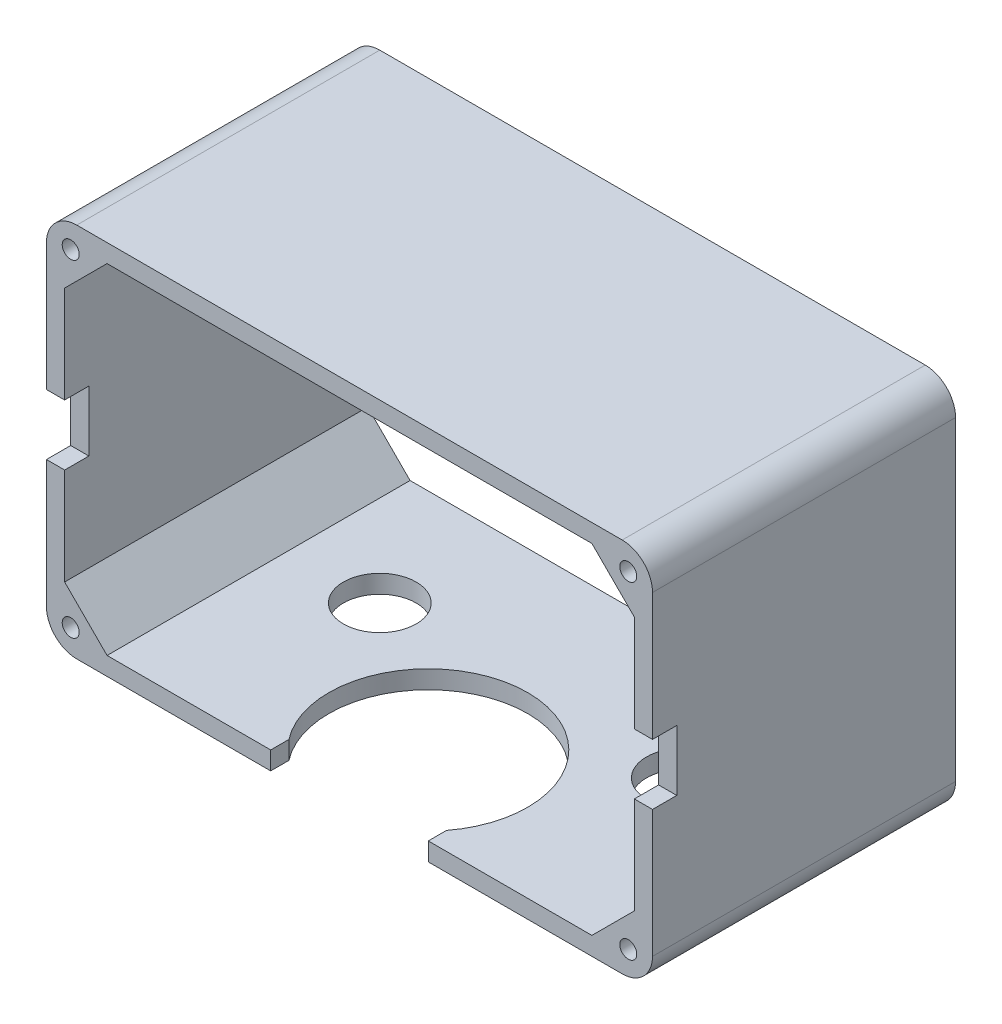
SolidWorks part; units mm, degrees
ref_plane "前视基准面" through (0, 0, 0) normal (0, 0, 1) x (1, 0, 0)
ref_plane "上视基准面" through (0, 0, 0) normal (0, 1, 0) x (1, 0, 0)
ref_plane "右视基准面" through (0, 0, 0) normal (1, 0, 0) x (0, 0, -1)
other "Configuration Table"
sketch "草图1" plane through (0, 0, 0) normal (0, 0, 1) x (1, 0, 0)
  line L1 (-45, 31) -> (45, 31)
  line L2 (-50, 26) -> (-50, -26)
  line L3 (-45, -31) -> (45, -31)
  line L4 (50, 26) -> (50, -26)
  line L5 (-50, 31) -> (50, -31) construction
  line L6 (-50, -31) -> (50, 31) construction
  line L7 (-42, 28) -> (42, 28)
  line L8 (-47, 23) -> (-47, -23)
  line L9 (-42, -28) -> (42, -28)
  line L10 (47, 23) -> (47, -23)
  line L11 (-47, 28) -> (47, -28) construction
  line L12 (-47, -28) -> (47, 28) construction
  arc A0 (-50, 26) -> (-45, 31) centre (-45, 26) cw
  arc A1 (50, 26) -> (45, 31) centre (45, 26) ccw
  arc A2 (45, -31) -> (50, -26) centre (45, -26) ccw
  arc A3 (-45, -31) -> (-50, -26) centre (-45, -26) cw
  arc A4 (-47, 23) -> (-42, 28) centre (-42, 23) cw
  arc A5 (47, 23) -> (42, 28) centre (42, 23) ccw
  arc A6 (42, -28) -> (47, -23) centre (42, -23) ccw
  arc A7 (-42, -28) -> (-47, -23) centre (-42, -23) cw
  point P0 (0, 0)
  point P18 (0, 0)
  dimension "D3" = 5
  dimension "D4" = 5
  dimension "D5" = 5
  dimension "D6" = 5
  dimension "D9" = 5
  dimension "D10" = 5
  dimension "D11" = 5
  dimension "D12" = 5
  dimension "D1" = 100
  dimension "D2" = 62
  dimension "D7" = 94
  dimension "D8" = 56
extrude "凸台-拉伸1" add sketch "草图1" along normal blind 50
sketch "草图3" plane through (0, 0, 50) normal (0, 0, 1) x (1, 0, 0)
  line L3 (-47, 28) -> (-47, 21)
  line L4 (-47, 23) -> (-47, -23) construction
  line L5 (-47, 21) -> (-40, 28)
  line L6 (42, 28) -> (-42, 28) construction
  line L7 (-40, 28) -> (-47, 28)
  dimension "D1" = 7
  dimension "D2" = 7
extrude "凸台-拉伸2" add sketch "草图3" against normal blind 50
sketch "草图4" plane through (0, 0, 50) normal (0, 0, 1) x (1, 0, 0)
  line L0 (45, 31) -> (-45, 31) construction
  line L1 (-50, 26) -> (-50, -26) construction
  circle A0 centre (-46, 27) radius 1.4
  dimension "D1" = 2.8
  dimension "D2" = 4
  dimension "D3" = 4
extrude "切除-拉伸1" cut sketch "草图4" against normal blind 60
mirror "镜向1" about plane through (0, 0, 0) normal (1, 0, 0) of "切除-拉伸1", "凸台-拉伸2"
mirror "镜向2" about plane through (0, 0, 0) normal (0, 1, 0) of "镜向1", "凸台-拉伸2", "切除-拉伸1"
sketch "草图6" plane through (0, -31, 0) normal (0, -1, 0) x (1, 0, 0)
  line L0 (-45, 50) -> (45, 50) construction
  line L1 (-13, 50) -> (13, 50)
  line L2 (-13, 50) -> (-13, 47)
  line L4 (13, 50) -> (13, 47)
  line L5 (0, 0) -> (0, 61.7001) construction
  arc A0 (-13, 47) -> (13, 47) centre (0, 37) ccw
  dimension "D4" = 13
  dimension "D1" = 26
  dimension "D2" = 13
extrude "切除-拉伸2" cut sketch "草图6" against normal blind 10
sketch "草图7" plane through (0, -31, 0) normal (0, -1, 0) x (1, 0, 0)
  line L0 (0, 0) -> (0, 67.2879) construction
  line L1 (-45, 0) -> (45, 0) construction
  circle A0 centre (-25, 20) radius 6
  circle A1 centre (25, 20) radius 6
  dimension "D1" = 12
  dimension "D2" = 50
  dimension "D3" = 20
extrude "切除-拉伸3" cut sketch "草图7" against normal blind 10
sketch "草图8" plane through (50, 0, 0) normal (1, 0, 0) x (0, 0, -1)
  line L0 (-50, -26) -> (-50, 26) construction
  line L1 (-50, 5) -> (-46, 5)
  line L2 (-50, 5) -> (-50, -5)
  line L3 (-50, -5) -> (-46, -5)
  line L4 (-46, 5) -> (-46, -5)
  line L5 (0, 0) -> (-65.3917, 0) construction
  dimension "D1" = 10
  dimension "D2" = 4
  dimension "D3" = 5
extrude "切除-拉伸4" cut sketch "草图8" against normal blind 100
